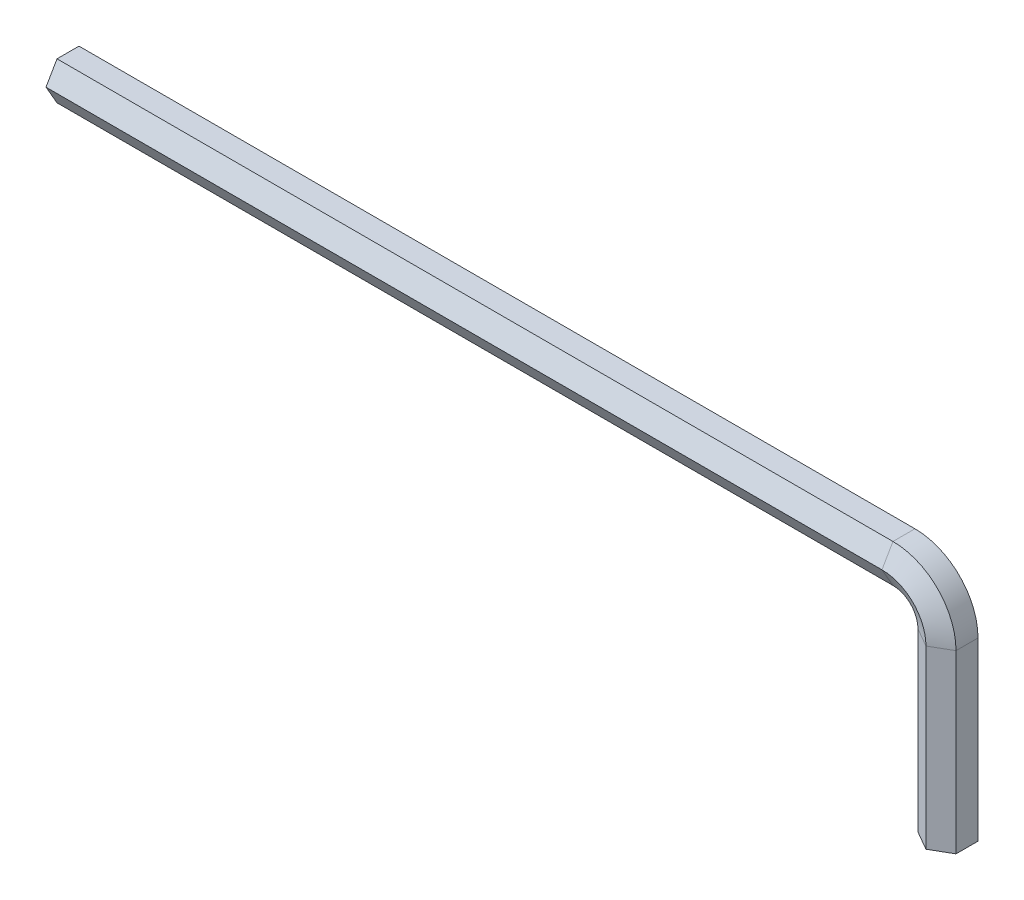
SolidWorks part; units mm, degrees
ref_plane "Front Plane" through (0, 0, 0) normal (0, 0, 1) x (1, 0, 0)
ref_plane "Top Plane" through (0, 0, 0) normal (0, 1, 0) x (1, 0, 0)
ref_plane "Right Plane" through (0, 0, 0) normal (1, 0, 0) x (0, 0, -1)
sketch "Sketch1" plane through (0, 0, 0) normal (0, 0, 1) x (1, 0, 0)
  line L0 (0, 0) -> (190, 0)
  line L1 (200, -10) -> (200, -50)
  arc A0 (200, -10) -> (190, 0) centre (190, -10) ccw
  point P6 (200, 0)
  dimension "D3" = 10
  dimension "D1" = 200
  dimension "D2" = 50
sketch "Sketch2" plane through (0, 0, 0) normal (1, 0, 0) x (0, 0, -1)
  line L1 (2.5, -4.3301) -> (5, 0)
  line L2 (5, 0) -> (2.5, 4.3301)
  line L3 (2.5, 4.3301) -> (-2.5, 4.3301)
  line L4 (-2.5, 4.3301) -> (-5, 0)
  line L5 (-5, 0) -> (-2.5, -4.3301)
  line L6 (-2.5, -4.3301) -> (2.5, -4.3301)
  circle A0 centre (0, 0) radius 4.3301 construction
  point P1 (0, 0)
  dimension "D1" = 5
sweep "Sweep1" add profiles "Sketch2" path "Sketch1"
